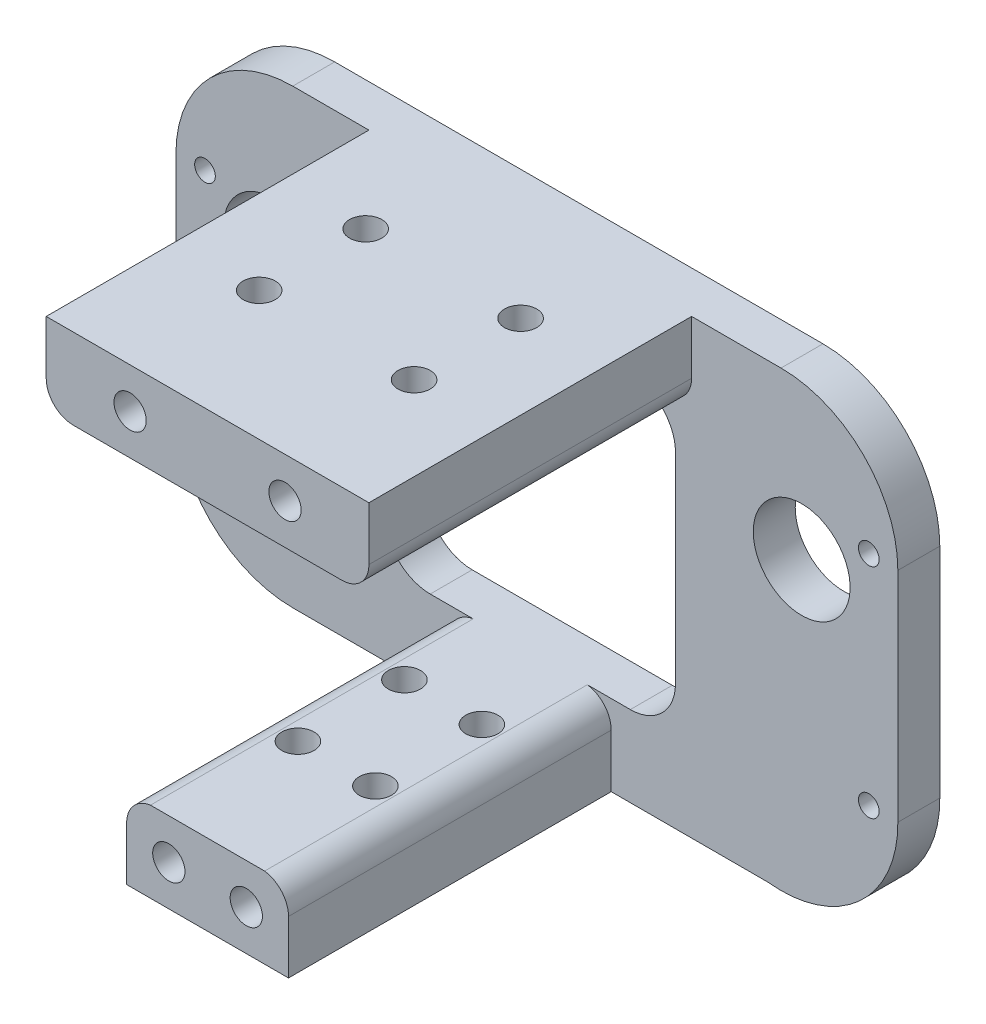
SolidWorks part; units mm, degrees
ref_plane "前视基准面" through (0, 0, 0) normal (0, 0, 1) x (1, 0, 0)
ref_plane "上视基准面" through (0, 0, 0) normal (0, 1, 0) x (1, 0, 0)
ref_plane "右视基准面" through (0, 0, 0) normal (1, 0, 0) x (0, 0, -1)
sketch "草图1" plane through (0, 0, 0) normal (0, 0, 1) x (1, 0, 0)
  line L0 (-36.8001, 35) -> (38.8503, 35)
  line L5 (56.9503, 16.9) -> (56.9503, -16.9)
  line L6 (-54.9, 16.9) -> (-54.9, -16.9)
  line L7 (-36.8001, -35) -> (36.8001, -35)
  line L8 (-15.5, 22.5) -> (15.5, 22.5)
  line L9 (22.5, 15.5) -> (22.5, -15.5)
  line L14 (15.5, -22.5) -> (-15.5, -22.5)
  line L15 (-22.5, 15.5) -> (-22.5, -15.5)
  arc A0 (-36.8001, 35) -> (-54.9, 16.9) centre (-36.8001, 16.9) ccw
  arc A1 (38.8503, 35) -> (56.9503, 16.9) centre (38.8503, 16.9) cw
  arc A2 (36.8001, -35) -> (56.9503, -16.9) centre (38.8507, -17.0166) ccw
  arc A3 (-36.8001, -35) -> (-54.9, -16.9) centre (-36.8001, -16.9) cw
  circle A4 centre (-50.4, 16.9) radius 1.6
  circle A5 centre (-40, 10.9) radius 7.5
  circle A6 centre (52.4503, 16.9) radius 1.6
  circle A7 centre (42.0503, 10.9) radius 7.5
  circle A8 centre (52.4503, -16.9) radius 1.6
  circle A9 centre (-50.4, -16.9) radius 1.6
  arc A10 (-15.5, 22.5) -> (-22.5, 15.5) centre (-15.5, 15.5) ccw
  arc A11 (15.5, 22.5) -> (22.5, 15.5) centre (15.5, 15.5) cw
  arc A12 (15.5, -22.5) -> (22.5, -15.5) centre (15.5, -15.5) ccw
  arc A13 (-15.5, -22.5) -> (-22.5, -15.5) centre (-15.5, -15.5) cw
  point P2 (0, 0)
extrude "凸台-拉伸1" add sketch "草图1" along normal blind 6.5
sketch "草图2" plane through (0, 0, 6.5) normal (0, 0, 1) x (1, 0, 0)
  line L0 (0, -22.5) -> (0, 22.5)
  line L1 (-15.5, -22.5) -> (15.5, -22.5) construction
  line L2 (15.5, 22.5) -> (-15.5, 22.5) construction
  line L9 (-20.8, 22.5) -> (20.8, 22.5)
  line L10 (-25, 26.7) -> (-25, 35)
  line L11 (38.8503, 35) -> (-36.8001, 35) construction
  line L12 (-25, 35) -> (25, 35)
  line L13 (25, 35) -> (25, 26.7)
  line L14 (-8.2601, -22.4601) -> (8.2601, -22.4601)
  line L15 (12.5399, -26.7399) -> (12.5399, -35)
  line L16 (-36.8001, -35) -> (36.8001, -35) construction
  line L17 (-12.5399, -35) -> (12.5399, -35)
  line L18 (-12.5399, -26.7399) -> (-12.5399, -35)
  line L19 (-12.5399, -35) -> (12.5399, -35)
  arc A0 (-25, 26.7) -> (-20.8, 22.5) centre (-20.8, 26.7) ccw
  arc A1 (25, 26.7) -> (20.8, 22.5) centre (20.8, 26.7) cw
  arc A2 (-8.2601, -22.4601) -> (-12.5399, -26.7399) centre (-8.2601, -26.7399) ccw
  arc A3 (8.2601, -22.4601) -> (12.5399, -26.7399) centre (8.2601, -26.7399) cw
extrude "凸台-拉伸2" add sketch "草图2" along normal blind 50
sketch "草图3" plane through (0, 0, 56.5) normal (0, 0, 1) x (1, 0, 0)
  circle A0 centre (-12, 28.75) radius 2.5
  circle A1 centre (12, 28.75) radius 2.5
  circle A2 centre (-6, -28.75) radius 2.5
  circle A3 centre (6, -28.75) radius 2.5
extrude "切除-拉伸1" cut sketch "草图3" against normal blind 10
sketch "草图5" plane through (0, 35, 0) normal (0, 1, 0) x (1, 0, 0)
  line L0 (38.8503, 0) -> (-36.8001, 0) construction
  line L1 (25, -56.5) -> (-25, -56.5) construction
  circle A0 centre (12, -20) radius 2.5
  circle A1 centre (-12, -20) radius 2.5
  circle A2 centre (12, -36.5) radius 2.5
  circle A3 centre (-12, -36.5) radius 2.5
  point P4 (0, 0)
  dimension "D1" = 20
  dimension "D2" = 20
  dimension "D3" = 20
  dimension "D4" = 20
extrude "切除-拉伸2" cut sketch "草图5" against normal up to next
sketch "草图6" plane through (0, -35, 0) normal (0, -1, 0) x (1, 0, 0)
  circle A2 centre (-6, 20) radius 2.5
  circle A3 centre (6, 20) radius 2.5
  circle A4 centre (-6, 36.5) radius 2.5
  circle A5 centre (6, 36.5) radius 2.5
extrude "切除-拉伸3" cut sketch "草图6" against normal up to next
